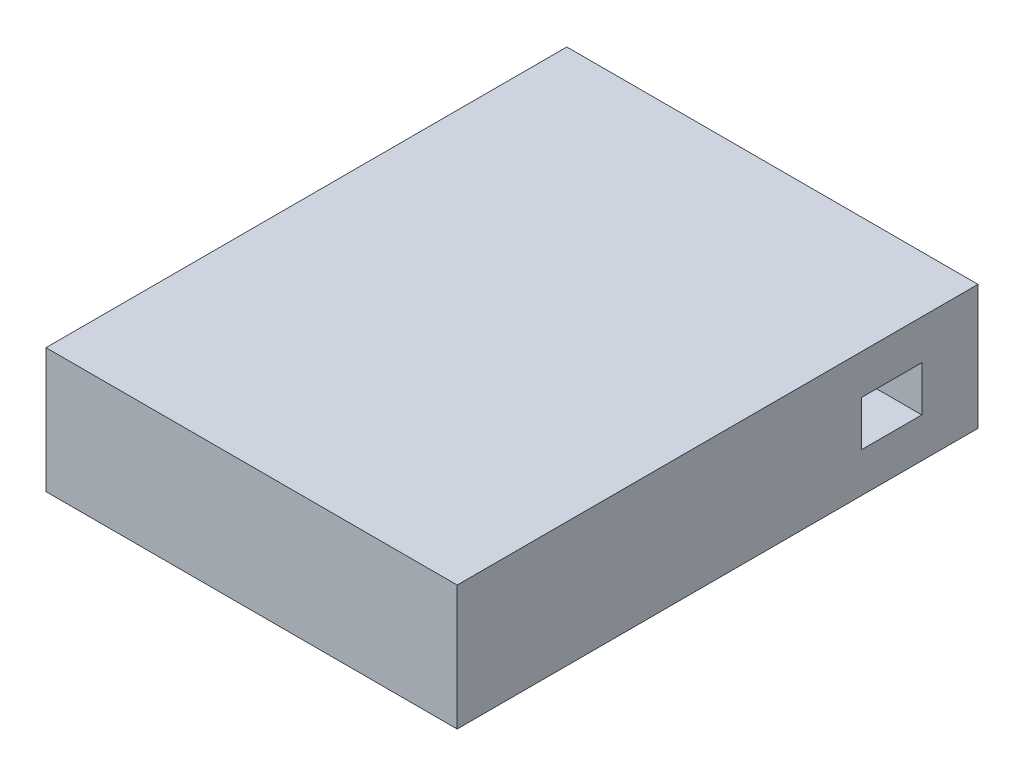
SolidWorks part; units mm, degrees
ref_plane "Front Plane" through (0, 0, 0) normal (0, 0, 1) x (1, 0, 0)
ref_plane "Top Plane" through (0, 0, 0) normal (0, 1, 0) x (1, 0, 0)
ref_plane "Right Plane" through (0, 0, 0) normal (1, 0, 0) x (0, 0, -1)
sketch "Sketch3" plane through (0, 0, 0) normal (0, 1, 0) x (1, 0, 0)
  line L1 (-15, -19) -> (15, -19)
  line L2 (-15, -19) -> (-15, 19)
  line L3 (-15, 19) -> (15, 19)
  line L4 (15, -19) -> (15, 19)
  line L5 (-15, -19) -> (15, 19) construction
  line L6 (-15, 19) -> (15, -19) construction
  point P0 (0, 0)
  dimension "D1" = 30
  dimension "D2" = 38
extrude "Boss-Extrude1" add sketch "Sketch3" along normal blind 9.1
sketch "Sketch4" plane through (15, 0, 0) normal (1, 0, 0) x (0, 0, -1)
  line L0 (-19, 9.1) -> (-19, 0) construction
  line L1 (14.9, 6.2) -> (10.5, 6.2)
  line L2 (14.9, 6.2) -> (14.9, 2.9)
  line L3 (14.9, 2.9) -> (10.5, 2.9)
  line L4 (10.5, 6.2) -> (10.5, 2.9)
  line L5 (14.9, 6.2) -> (10.5, 2.9) construction
  line L6 (14.9, 2.9) -> (10.5, 6.2) construction
  line L7 (-19, 4.55) -> (10.5, 4.55) construction
  point P0 (12.7, 4.55)
  dimension "D1" = 3.3
  dimension "D2" = 4.4
  dimension "D3" = 29.5
extrude "Cut-Extrude1" cut sketch "Sketch4" against normal blind 46.1
